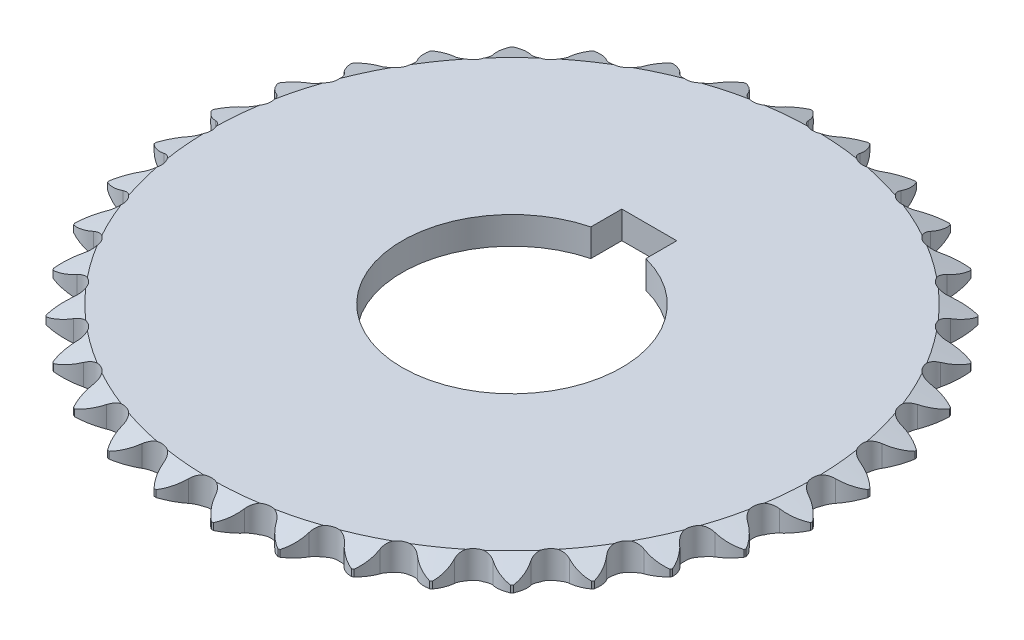
SolidWorks part; units mm, degrees
ref_plane "Front Plane" through (0, 0, 0) normal (0, 0, 1) x (1, 0, 0)
ref_plane "Top Plane" through (0, 0, 0) normal (0, 1, 0) x (1, 0, 0)
ref_plane "Right Plane" through (0, 0, 0) normal (1, 0, 0) x (0, 0, -1)
sketch "Sketch1" plane through (0, 0, 0) normal (0, 1, 0) x (1, 0, 0)
  circle A0 centre (0, 0) radius 38.1
  dimension "D1" = 76.2
extrude "Base Circle" add sketch "Sketch1" along normal mid plane 3.175 contours A0
sketch "Sketch2" plane through (0, 1.5875, 0) normal (0, 1, 0) x (1, 0, 0)
  line L0 (0, 0) -> (0, 36.449) construction
  line L1 (0, 36.449) -> (-6.3293, 35.8953) construction
  line L2 (-6.3293, 35.8953) -> (0, 0) construction
  line L3 (0, 0) -> (-3.1647, 36.1721) construction
  circle A0 centre (0, 0) radius 36.449 construction
  arc A1 (0.4028, 38.0979) -> (-0.4028, 38.0979) centre (0, 36.449) ccw
  circle A2 centre (0, 0) radius 34.6666 construction
  arc A4 (-3.3293, 38.0546) -> (-2.6904, 30.7519) centre (0, 34.6666) ccw construction
  circle A5 centre (0, 0) radius 38.1 construction
  arc A6 (-2.6904, 30.7519) -> (-3.3293, 38.0546) centre (-6.0198, 34.1399) ccw construction
  arc A7 (3.2035, 37.9651) -> (-3.2035, 37.9651) centre (0, 0) ccw
  circle A8 centre (0, 0) radius 38.2 construction
  arc A9 (-3.2035, 37.9651) -> (-1.5848, 35.8411) centre (-6.0198, 34.1399) cw
  arc A10 (3.2035, 37.9651) -> (1.5848, 35.8411) centre (6.0198, 34.1399) ccw
  arc A11 (-1.5848, 35.8411) -> (1.5848, 35.8411) centre (0, 36.449) ccw
  circle A13 centre (0, 0) radius 38.1 construction
  point P23 (36.4352, 11.1394)
  circle M14 centre (0, 0) radius 38.1
  dimension "D1" = 72.898
  dimension "D2" = 3.3947
  dimension "D4" = 0.1
  dimension "D3" = 10
extrude "Tooth Profile Cut" cut sketch "Sketch2" against normal through all both and the other way through all contours A9 A11 A10 M14
pattern_circular "Tooth Profile Cut Pattern" count 36 over 360 about axis through (0, 0, 0) along (0, 1, 0) of "Tooth Profile Cut"
sketch "Sketch3" plane through (0, 0, 0) normal (1, 0, 0) x (0, 0, -1)
  line L0 (0, 0) -> (38.1, 0) construction
  line L1 (38.1, -0.3969) -> (38.1, 0.3969) construction
  line L2 (38.1, -0.3969) -> (34.925, -1.5875)
  line L3 (34.925, -1.5875) -> (34.925, 1.5875) construction
  line L4 (34.925, 1.5875) -> (38.1, 0.3969)
  line L5 (38.1, 0.3969) -> (38.1, 1.5875)
  line L6 (38.1, 1.5875) -> (34.925, 1.5875)
  line L7 (38.1, -0.3969) -> (38.1, -1.5875)
  line L8 (38.1, -1.5875) -> (34.925, -1.5875)
  point P5 (38.1, 0)
  dimension "D1" = 38.1
  dimension "D2" = 0.7937
  dimension "D3" = 3.175
  dimension "D4" = 3.175
revolve "Tooth Chamfer" cut sketch "Sketch3" angle 360 about axis through (0, 1.5875, 0) along (0, -1, 0)
sketch "Sketch4" plane through (0, 1.5875, 0) normal (0, 1, 0) x (1, 0, 0)
  line L0 (0, 12.7) -> (0, 15.875) construction
  line L1 (0, 15.875) -> (-3.175, 15.875)
  line L2 (-3.175, 15.875) -> (-3.175, 12.2967)
  line L3 (0, 15.875) -> (3.175, 15.875)
  line L4 (3.175, 15.875) -> (3.175, 12.2967)
  arc A0 (-3.175, 12.2967) -> (3.175, 12.2967) centre (0, 0) ccw
  dimension "D1" = 25.4
  dimension "D2" = 3.175
  dimension "D3" = 12.7
extrude "Shaft hole with keyway" cut sketch "Sketch4" against normal through all both and the other way through all
